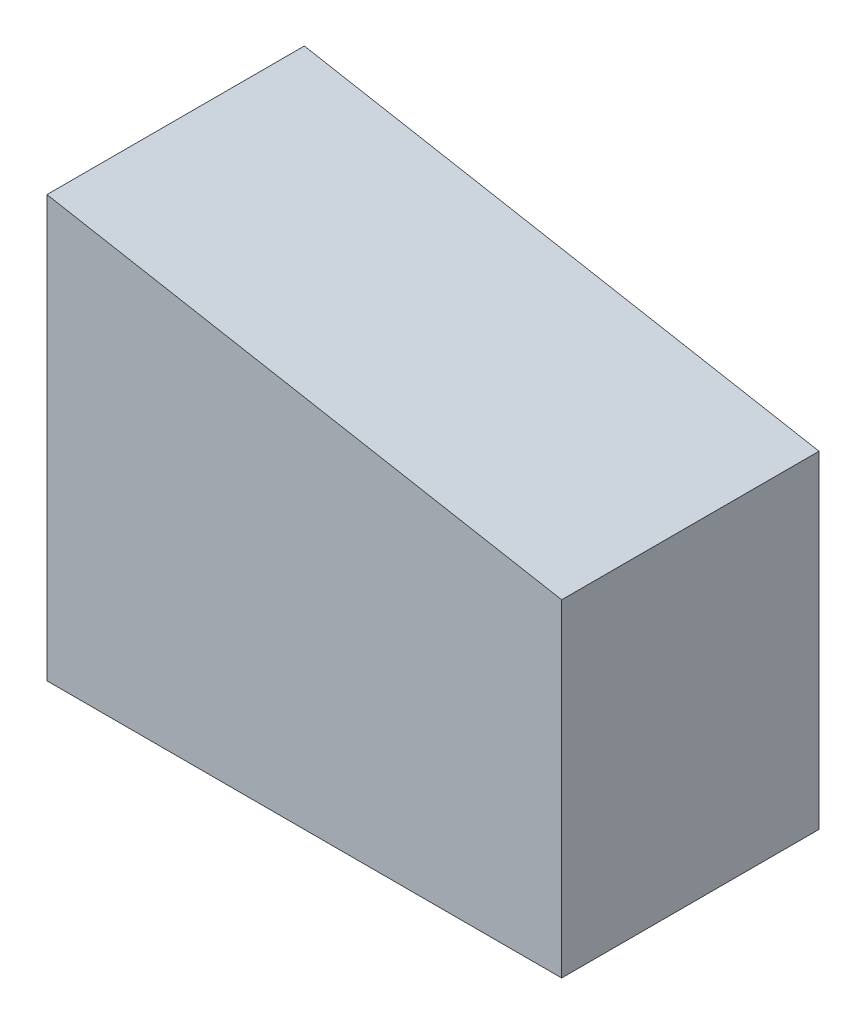
SolidWorks part; units mm, degrees
material "ﾁｰｸ材"
ref_plane "正面" through (0, 0, 0) normal (0, 0, 1) x (1, 0, 0)
ref_plane "平面" through (0, 0, 0) normal (0, 1, 0) x (1, 0, 0)
ref_plane "右側面" through (0, 0, 0) normal (1, 0, 0) x (0, 0, -1)
sketch "ｽｹｯﾁ1" plane through (0, 0, 0) normal (0, 0, 1) x (1, 0, 0)
  line L0 (0, 0) -> (11, 0)
  line L1 (11, 0) -> (11, 7)
  line L2 (11, 7) -> (0, 9)
  line L3 (0, 9) -> (0, 0)
  dimension "D1" = 11
  dimension "D2" = 7
  dimension "D3" = 9
extrude "ﾎﾞｽ - 押し出し1" add sketch "ｽｹｯﾁ1" along normal blind 5.5
